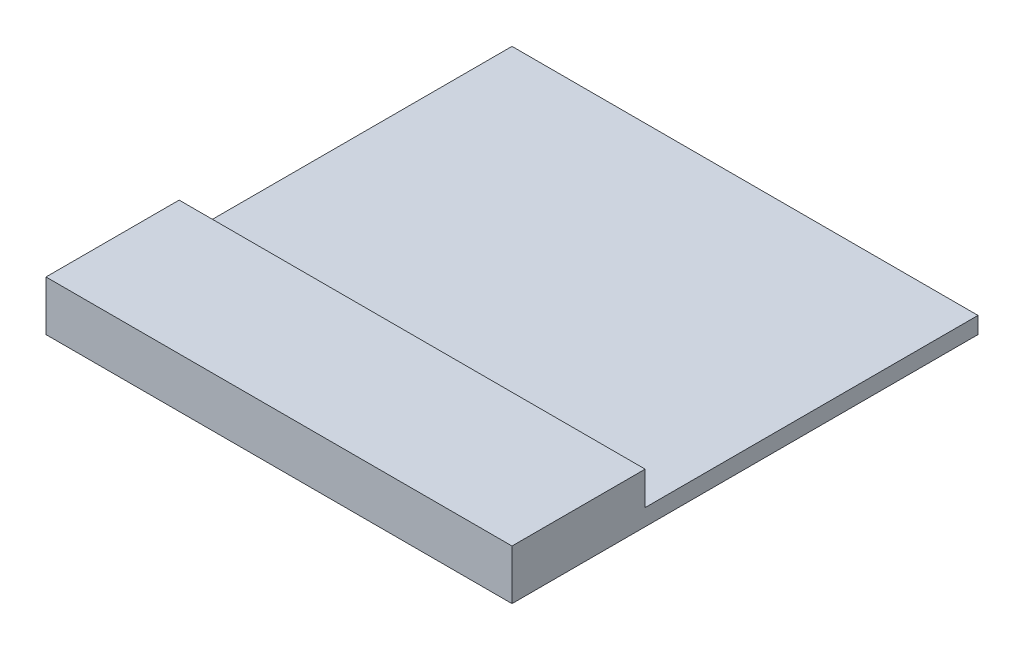
SolidWorks part; units mm, degrees
ref_plane "Front Plane" through (0, 0, 0) normal (0, 0, 1) x (1, 0, 0)
ref_plane "Top Plane" through (0, 0, 0) normal (0, 1, 0) x (1, 0, 0)
ref_plane "Right Plane" through (0, 0, 0) normal (1, 0, 0) x (0, 0, -1)
sketch "Sketch1" plane through (0, 0, 0) normal (0, 1, 0) x (1, 0, 0)
  line L1 (0, 0) -> (28, 0)
  line L2 (0, 0) -> (0, 28)
  line L3 (0, 28) -> (28, 28)
  line L4 (28, 0) -> (28, 28)
  dimension "D1" = 28
  dimension "D2" = 28
extrude "Boss-Extrude1" add sketch "Sketch1" along normal blind 1
sketch "Sketch2" plane through (0, 1, 0) normal (0, 1, 0) x (1, 0, 0)
  line L0 (28, 0) -> (28, 28) construction
  line L1 (0, 0) -> (28, 0)
  line L2 (0, 0) -> (0, 8)
  line L3 (0, 8) -> (28, 8)
  line L4 (28, 0) -> (28, 8)
  dimension "D1" = 8
extrude "Boss-Extrude2" add sketch "Sketch2" along normal blind 2
